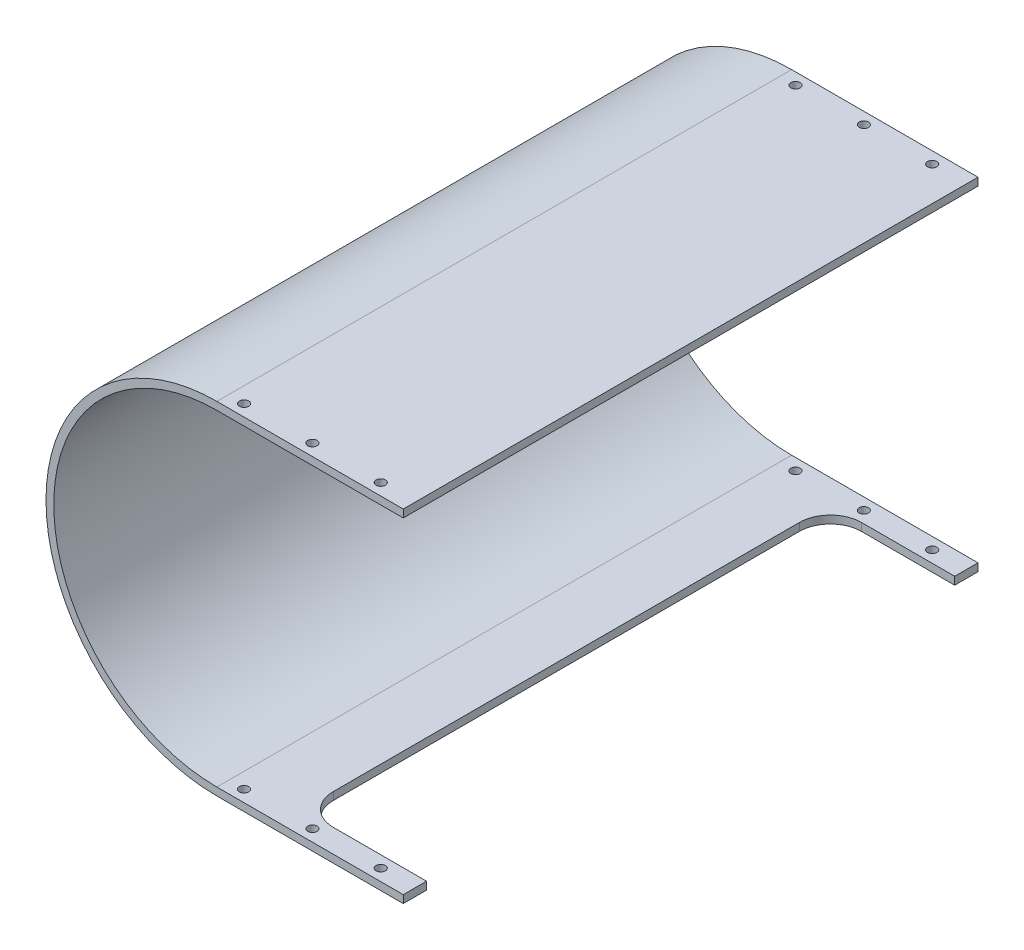
SolidWorks part; units mm, degrees
ref_plane "Front Plane" through (0, 0, 0) normal (0, 0, 1) x (1, 0, 0)
ref_plane "Top Plane" through (0, 0, 0) normal (0, 1, 0) x (1, 0, 0)
ref_plane "Right Plane" through (0, 0, 0) normal (1, 0, 0) x (0, 0, -1)
sketch "Sketch1" plane through (0, 0, 0) normal (0, 0, 1) x (1, 0, 0)
  line L0 (-60, 55) -> (0, 55)
  line L1 (0, 55) -> (0, 52.5)
  line L2 (0, -55) -> (-60, -55)
  line L3 (-60, -52.5) -> (0, -52.5)
  line L4 (-60, 52.5) -> (0, 52.5)
  line L5 (0, -52.5) -> (0, -55)
  arc A0 (-60, 52.5) -> (-60, -52.5) centre (-60, 0) ccw
  arc A1 (-60, 55) -> (-60, -55) centre (-60, 0) ccw
  dimension "D1" = 105
  dimension "D2" = 110
  dimension "D3" = 60
extrude "Boss-Extrude1" add sketch "Sketch1" along normal mid plane 185
sketch "Sketch2" plane through (0, -55, 0) normal (0, -1, 0) x (1, 0, 0)
  line L1 (-40, 85) -> (40, 85)
  line L2 (-40, 85) -> (-40, -85)
  line L3 (-40, -85) -> (40, -85)
  line L4 (40, 85) -> (40, -85)
  line L5 (-40, 85) -> (40, -85) construction
  line L6 (-40, -85) -> (40, 85) construction
  point P0 (0, 0)
  dimension "D1" = 80
  dimension "D2" = 170
extrude "Cut-Extrude1" cut sketch "Sketch2" against normal up to surface (2.5 mm away) up to face at (-30, -52.5, 0)
fillet "Fillet1" radius 10 2 edges at (-40, -53.75, -85) (-40, -53.75, 85)
sketch "Sketch3" plane through (0, 0, 0) normal (0, 1, 0) x (1, 0, 0)
  line L0 (0, 88.75) -> (-55, 88.75) construction
  line L1 (0, 92.5) -> (-60, 92.5) construction
  line L2 (-134.0249, 0) -> (85.3232, 0) construction
  circle A1 centre (-55, 88.75) radius 1.5
  circle A2 centre (-44, 88.75) radius 1.5 [skipped]
  circle A3 centre (-33, 88.75) radius 1.5
  circle A4 centre (-22, 88.75) radius 1.5 [skipped]
  circle A5 centre (-11, 88.75) radius 1.5
  circle A6 centre (0, 88.75) radius 1.5 [skipped]
  circle A7 centre (11, 88.75) radius 1.5 [skipped]
  circle A8 centre (22, 88.75) radius 1.5 [skipped]
  circle A9 centre (33, 88.75) radius 1.5 [skipped]
  circle A10 centre (44, 88.75) radius 1.5 [skipped]
  circle A11 centre (55, 88.75) radius 1.5 [skipped]
  circle A12 centre (-11, -88.75) radius 1.5
  circle A13 centre (-33, -88.75) radius 1.5
  circle A14 centre (-55, -88.75) radius 1.5
  dimension "D1" = 55
  dimension "D2" = 3
  dimension "D4" = 3.75
  dimension "D3" = 11
extrude "Cut-Extrude2" cut sketch "Sketch3" against normal through all both and the other way through all
